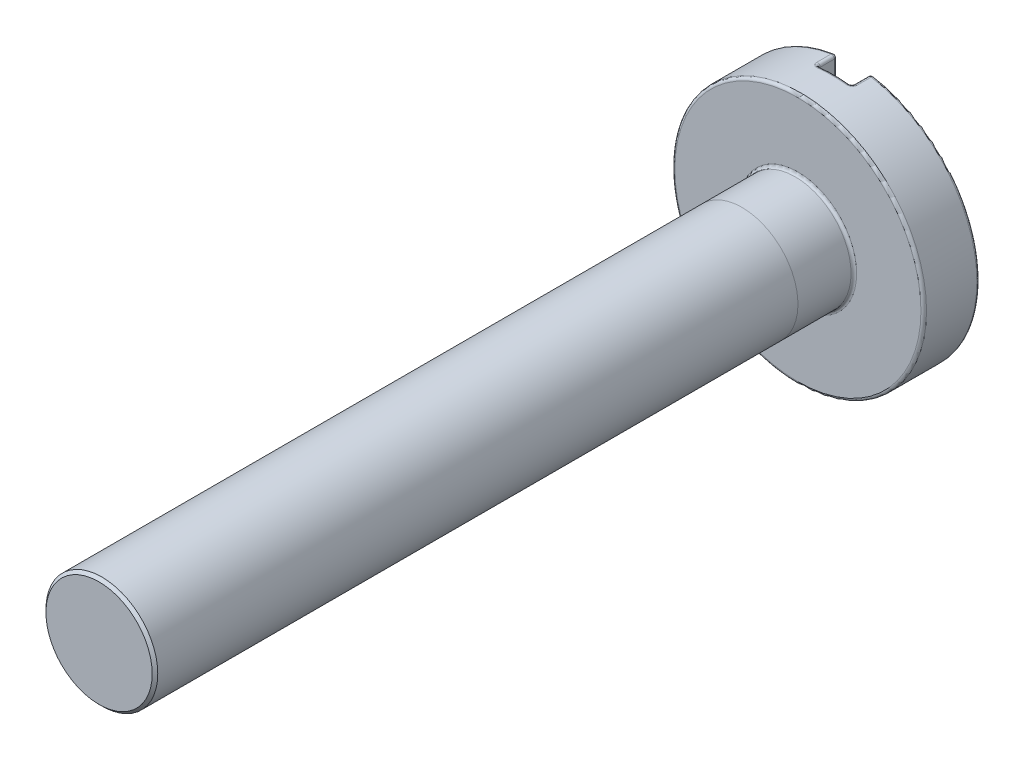
SolidWorks part; units mm, degrees
ref_plane "Front Plane" through (0, 0, 0) normal (0, 0, 1) x (1, 0, 0)
ref_plane "Top Plane" through (0, 0, 0) normal (0, 1, 0) x (1, 0, 0)
ref_plane "Right Plane" through (0, 0, 0) normal (1, 0, 0) x (0, 0, -1)
sketch "Sketch1" plane through (0, 0, 0) normal (0, 0, 1) x (1, 0, 0)
  circle A0 centre (0, 0) radius 1
  dimension "D1" = 2
extrude "Boss-Extrude1" add sketch "Sketch1" along normal blind 12.5
sketch "Sketch2" plane through (0, 0, 0) normal (0, 0, 1) x (1, 0, 0)
  circle A2 centre (0, 0) radius 2.25
  circle A3 centre (0, 0) radius 2.25
  dimension "D1" = 1.25
extrude "Boss-Extrude2" add sketch "Sketch2" against normal blind 1
sketch "Sketch3" plane through (0, 0, -1) normal (0, 0, -1) x (-1, 0, 0)
  line L1 (-0.3, 4.1969) -> (0.3, 4.1969)
  line L2 (-0.3, 4.1969) -> (-0.3, -4.1969)
  line L3 (-0.3, -4.1969) -> (0.3, -4.1969)
  line L4 (0.3, 4.1969) -> (0.3, -4.1969)
  line L5 (-0.3, 4.1969) -> (0.3, -4.1969) construction
  line L6 (-0.3, -4.1969) -> (0.3, 4.1969) construction
  point P0 (0, 0)
  dimension "D1" = 0.6
extrude "Cut-Extrude1" cut sketch "Sketch3" against normal blind 0.35
fillet "Fillet1" radius 0.05 13 edges at (0.3, 2.2299, -0.825) (0.3, -2.2299, -0.825) (-0.3, -2.2299, -0.825) (-0.3, 2.2299, -0.825) (0, -2.25, -0.65) (0, 2.25, -0.65) (0.3, 0, -0.65) (-0.3, 0, -0.65) (0.3, 0, -1) (2.25, 0, -1) (-0.3, 0, -1) (-2.25, 0, -1) (1, 0, 0)
fillet "Fillet2" radius 0.05 1 edges at (2.25, 0, 0)
chamfer "Chamfer1" distance 0.05 angle 45 1 edges at (1, 0, 12.5)
sketch "Sketch4" plane through (0, 0, 0) normal (1, 0, 0) x (0, 0, -1)
  line L0 (-1, 3.701) -> (-1, -3.2348)
  line L1 (-12.5, 0.95) -> (-12.5, -0.95) construction
  dimension "D1" = 11.5
split line "Split Line1"
